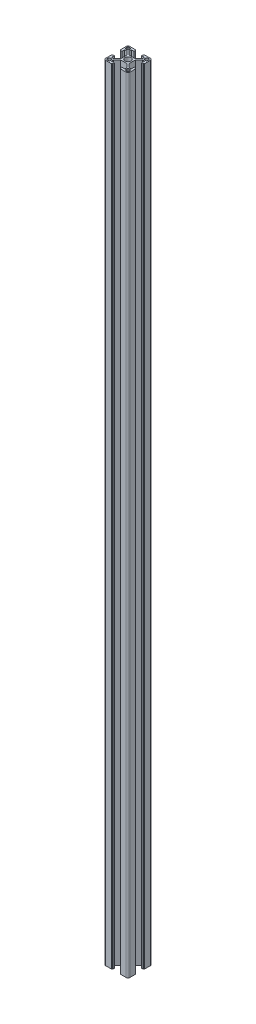
SolidWorks part; units mm, degrees
material "氧化铝"
ref_plane "前视基准面" through (0, 0, 0) normal (0, 0, 1) x (1, 0, 0)
ref_plane "上视基准面" through (0, 0, 0) normal (0, 1, 0) x (1, 0, 0)
ref_plane "右视基准面" through (0, 0, 0) normal (1, 0, 0) x (0, 0, -1)
other "Configuration Table"
sketch "草图1" plane through (0, 0, 0) normal (0, 1, 0) x (1, 0, 0)
  line L0 (-25.7983, 0) -> (25.4552, 0) construction
  line L1 (0, 19.6731) -> (0, -18.6486) construction
  line L2 (-3.6, 10) -> (-8.5, 10)
  line L3 (-10, 8.5) -> (-10, 3.6)
  line L4 (10, 8.5) -> (10, 3.6)
  line L5 (3.6, 10) -> (8.5, 10)
  line L6 (3.6, -10) -> (8.5, -10)
  line L7 (10, -8.5) -> (10, -3.6)
  line L8 (-10, -8.5) -> (-10, -3.6)
  line L9 (-3.6, -10) -> (-8.5, -10)
  line L10 (-8.2, 3.1) -> (-8.2, 5.5)
  line L11 (-5.5, 8.2) -> (-3.1, 8.2)
  line L12 (-2.6515, 3.5) -> (2.6515, 3.5)
  line L13 (-3.5, 2.6515) -> (-3.5, -2.6515)
  line L14 (-8.2, 5.5) -> (-6.3485, 5.5)
  line L15 (-6.3485, 5.5) -> (-3.5, 2.6515)
  line L16 (-22.816, 22.816) -> (22.278, -22.278) construction
  line L17 (-5.5, 6.3485) -> (-2.6515, 3.5)
  line L18 (-5.5, 8.2) -> (-5.5, 6.3485)
  line L19 (5.5, 8.2) -> (5.5, 6.3485)
  line L20 (8.2, 5.5) -> (6.3485, 5.5)
  line L21 (8.2, 3.1) -> (8.2, 5.5)
  line L22 (6.3485, 5.5) -> (3.5, 2.6515)
  line L23 (5.5, 6.3485) -> (2.6515, 3.5)
  line L24 (5.5, 8.2) -> (3.1, 8.2)
  line L25 (3.5, 2.6515) -> (3.5, -2.6515)
  line L27 (-9.4, 3.6) -> (-10, 3.6)
  line L31 (8.2, -3.1) -> (8.2, -5.5)
  line L32 (8.2, -5.5) -> (6.3485, -5.5)
  line L33 (5.5, -8.2) -> (5.5, -6.3485)
  line L34 (5.5, -8.2) -> (3.1, -8.2)
  line L37 (-5.5, -8.2) -> (-3.1, -8.2)
  line L38 (-5.5, -8.2) -> (-5.5, -6.3485)
  line L39 (6.3485, -5.5) -> (3.5, -2.6515)
  line L40 (5.5, -6.3485) -> (2.6515, -3.5)
  line L41 (-5.5, -6.3485) -> (-2.6515, -3.5)
  line L42 (-6.3485, -5.5) -> (-3.5, -2.6515)
  line L43 (-8.2, -5.5) -> (-6.3485, -5.5)
  line L44 (-8.2, -3.1) -> (-8.2, -5.5)
  line L46 (-2.6515, -3.5) -> (2.6515, -3.5)
  line L47 (-7.4, 9.1) -> (-8.1, 9.1)
  line L48 (-6.4, 8.1) -> (-6.4, 7.4)
  line L49 (-7.4, 6.4) -> (-8.1, 6.4)
  line L50 (-9.1, 7.4) -> (-9.1, 8.1)
  line L51 (9.1, 7.4) -> (9.1, 8.1)
  line L52 (7.4, 6.4) -> (8.1, 6.4)
  line L53 (6.4, 8.1) -> (6.4, 7.4)
  line L54 (7.4, 9.1) -> (8.1, 9.1)
  line L55 (7.4, -9.1) -> (8.1, -9.1)
  line L56 (6.4, -8.1) -> (6.4, -7.4)
  line L57 (7.4, -6.4) -> (8.1, -6.4)
  line L58 (9.1, -7.4) -> (9.1, -8.1)
  line L59 (-9.1, -7.4) -> (-9.1, -8.1)
  line L60 (-7.4, -6.4) -> (-8.1, -6.4)
  line L61 (-6.4, -8.1) -> (-6.4, -7.4)
  line L62 (-7.4, -9.1) -> (-8.1, -9.1)
  line L63 (-9.4, 3.6) -> (-9.4, 3.1)
  line L64 (-9.4, 3.1) -> (-8.2, 3.1)
  line L65 (-9.4, -3.1) -> (-8.2, -3.1)
  line L66 (-9.4, -3.6) -> (-9.4, -3.1)
  line L67 (-9.4, -3.6) -> (-10, -3.6)
  line L68 (9.4, -3.1) -> (8.2, -3.1)
  line L69 (9.4, -3.6) -> (9.4, -3.1)
  line L70 (9.4, -3.6) -> (10, -3.6)
  line L71 (9.4, 3.1) -> (8.2, 3.1)
  line L72 (9.4, 3.6) -> (9.4, 3.1)
  line L73 (9.4, 3.6) -> (10, 3.6)
  line L74 (-3.1, 9.4) -> (-3.1, 8.2)
  line L75 (-3.6, 9.4) -> (-3.1, 9.4)
  line L76 (-3.6, 9.4) -> (-3.6, 10)
  line L77 (3.1, 9.4) -> (3.1, 8.2)
  line L78 (3.6, 9.4) -> (3.1, 9.4)
  line L79 (3.6, 9.4) -> (3.6, 10)
  line L80 (-3.6, -9.4) -> (-3.1, -9.4)
  line L81 (3.1, -9.4) -> (3.1, -8.2)
  line L82 (3.6, -9.4) -> (3.1, -9.4)
  line L83 (3.6, -9.4) -> (3.6, -10)
  line L84 (-3.1, -9.4) -> (-3.1, -8.2)
  line L85 (-3.6, -9.4) -> (-3.6, -10)
  circle A0 centre (0, 0) radius 2.5
  arc A1 (-8.5, -10) -> (-10, -8.5) centre (-8.5, -8.5) cw
  arc A2 (8.5, -10) -> (10, -8.5) centre (8.5, -8.5) ccw
  arc A3 (8.5, 10) -> (10, 8.5) centre (8.5, 8.5) cw
  arc A4 (-8.5, 10) -> (-10, 8.5) centre (-8.5, 8.5) ccw
  arc A5 (-8.1, 9.1) -> (-9.1, 8.1) centre (-8.1, 8.1) ccw
  arc A6 (-9.1, 7.4) -> (-8.1, 6.4) centre (-8.1, 7.4) ccw
  arc A7 (-7.4, 6.4) -> (-6.4, 7.4) centre (-7.4, 7.4) ccw
  arc A8 (-7.4, 9.1) -> (-6.4, 8.1) centre (-7.4, 8.1) cw
  arc A9 (7.4, 9.1) -> (6.4, 8.1) centre (7.4, 8.1) ccw
  arc A10 (7.4, 6.4) -> (6.4, 7.4) centre (7.4, 7.4) cw
  arc A11 (9.1, 7.4) -> (8.1, 6.4) centre (8.1, 7.4) cw
  arc A12 (8.1, 9.1) -> (9.1, 8.1) centre (8.1, 8.1) cw
  arc A13 (8.1, -9.1) -> (9.1, -8.1) centre (8.1, -8.1) ccw
  arc A14 (9.1, -7.4) -> (8.1, -6.4) centre (8.1, -7.4) ccw
  arc A15 (7.4, -6.4) -> (6.4, -7.4) centre (7.4, -7.4) ccw
  arc A16 (7.4, -9.1) -> (6.4, -8.1) centre (7.4, -8.1) cw
  arc A17 (-7.4, -9.1) -> (-6.4, -8.1) centre (-7.4, -8.1) ccw
  arc A18 (-7.4, -6.4) -> (-6.4, -7.4) centre (-7.4, -7.4) cw
  arc A19 (-9.1, -7.4) -> (-8.1, -6.4) centre (-8.1, -7.4) cw
  arc A20 (-8.1, -9.1) -> (-9.1, -8.1) centre (-8.1, -8.1) cw
  point P26 (0, 0)
  point P30 (0, 0)
  point P41 (-19.225, 7.9035)
  point P73 (0, 0)
  point P75 (0, 0)
  point P76 (0, 0)
  point P77 (-8.2, -2.6515)
  point P78 (0, 0)
  point P115 (-8.2, 2.9167)
  point P118 (0, 0)
  point P119 (8.2, -3.1698)
  point P130 (0, 0)
  point P131 (0, 0)
  point P132 (-3.1763, 8.2)
  point P141 (-3.1634, -8.2)
  dimension "D1" = 5
  dimension "D6" = 1.8
  dimension "D12" = 1
  dimension "D8" = 1.5
  dimension "D2" = 7.2
  dimension "D3" = 7.2
  dimension "D4" = 11
  dimension "D5" = 6.5
  dimension "D7" = 7
  dimension "D9" = 0.9
  dimension "D10" = 1.2
  dimension "D11" = 0.9
  dimension "D13" = 6.2
  dimension "D14" = 1.2
extrude "凸台-拉伸1" add sketch "草图1" along normal blind 650
